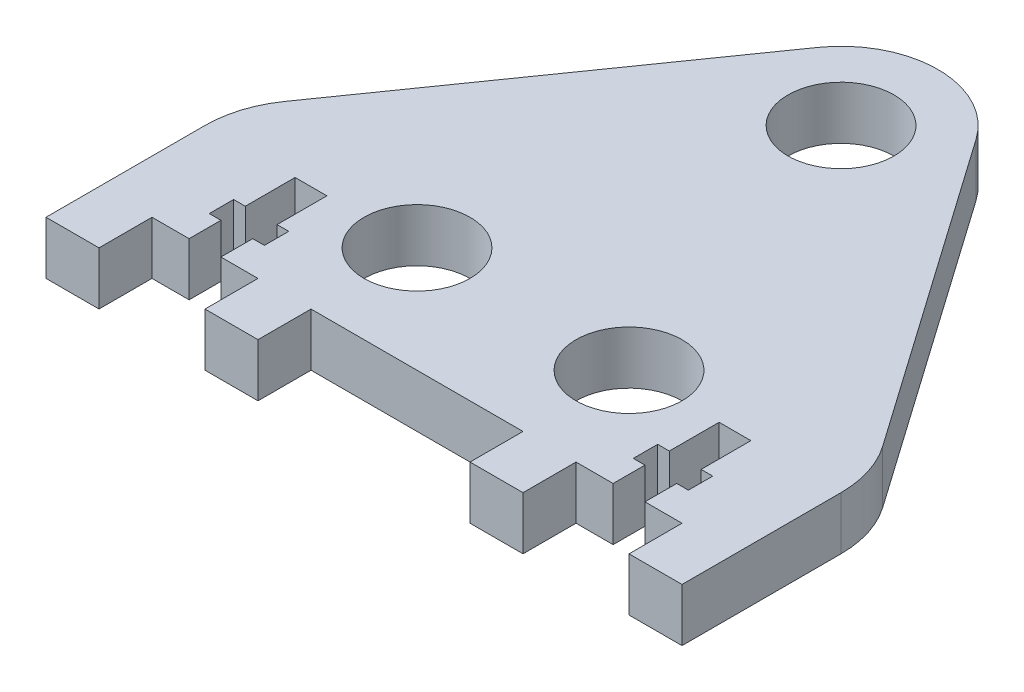
SolidWorks part; units mm, degrees
ref_plane "Front Plane" through (0, 0, 0) normal (0, 0, 1) x (1, 0, 0)
ref_plane "Top Plane" through (0, 0, 0) normal (0, 1, 0) x (1, 0, 0)
ref_plane "Right Plane" through (0, 0, 0) normal (1, 0, 0) x (0, 0, -1)
sketch "Sketch1" plane through (0, 0, 0) normal (0, 1, 0) x (1, 0, 0)
  line L1 (-30, 10) -> (-30, -5)
  line L2 (-30, -5) -> (-25, -5)
  line L3 (-10, -5) -> (-10, 0)
  line L4 (-10, 0) -> (10, 0)
  line L5 (10, -5) -> (10, 0)
  line L6 (30, -5) -> (25, -5)
  line L7 (30, 10) -> (30, -5)
  line L11 (0, 0) -> (0, 43.6328) construction
  line L13 (-28.1874, 15.7417) -> (-7.4911, 45.2534)
  line L14 (7.4911, 45.2534) -> (28.1874, 15.7417)
  line L36 (-25, -5) -> (-25, 0)
  line L37 (-25, 0) -> (-21.5, 0)
  line L38 (-21.5, 0) -> (-21.5, 3)
  line L39 (-21.5, 3) -> (-22.6, 3)
  line L40 (-22.6, 3) -> (-22.6, 5.3)
  line L41 (-22.6, 5.3) -> (-21.5, 5.3)
  line L42 (-21.5, 5.3) -> (-21.5, 10)
  line L43 (-21.5, 10) -> (-18.5, 10)
  line L44 (-18.5, 10) -> (-18.5, 5.3)
  line L45 (-18.5, 5.3) -> (-17.4, 5.3)
  line L46 (-17.4, 5.3) -> (-17.4, 3)
  line L47 (-17.4, 3) -> (-18.5, 3)
  line L48 (-18.5, 3) -> (-18.5, 0)
  line L49 (-18.5, 0) -> (-15, 0)
  line L50 (-15, 0) -> (-15, -5)
  line L51 (-15, -5) -> (-10, -5)
  line L52 (25, 0) -> (21.5, 0)
  line L53 (21.5, 0) -> (21.5, 3)
  line L54 (21.5, 3) -> (22.6, 3)
  line L55 (22.6, 5.3) -> (21.5, 5.3)
  line L56 (22.6, 3) -> (22.6, 5.3)
  line L57 (21.5, 5.3) -> (21.5, 10)
  line L58 (21.5, 10) -> (18.5, 10)
  line L59 (18.5, 10) -> (18.5, 5.3)
  line L60 (18.5, 5.3) -> (17.4, 5.3)
  line L61 (17.4, 5.3) -> (17.4, 3)
  line L62 (17.4, 3) -> (18.5, 3)
  line L63 (18.5, 3) -> (18.5, 0)
  line L64 (18.5, 0) -> (15, 0)
  line L65 (15, 0) -> (15, -5)
  line L66 (25, -5) -> (25, 0)
  line L67 (15, -5) -> (10, -5)
  arc A0 (-7.4911, 45.2534) -> (7.4911, 45.2534) centre (0, 40) cw
  circle A2 centre (0, 40) radius 5
  arc A3 (30, 10) -> (28.1874, 15.7417) centre (20, 10) ccw
  arc A4 (-30, 10) -> (-28.1874, 15.7417) centre (-20, 10) cw
  circle A5 centre (-10, 10) radius 5
  circle A6 centre (10, 10) radius 5
  point P0 (0, 0)
  point P68 (-16.75, 0)
  point P72 (-17.95, 3)
  point P73 (-22.05, 5.3)
  point P74 (-22.05, 3)
  point P78 (22.05, 3)
  point P80 (22.05, 5.3)
  point P88 (17.95, 3)
  point P91 (16.75, 0)
  dimension "D1" = 5
  dimension "D4" = 10
  dimension "D6" = 60
  dimension "D24" = 10
  dimension "D2" = 5
  dimension "D3" = 40
  dimension "D5" = 10
  dimension "D7" = 10
  dimension "D12" = 5
  dimension "D13" = 5
  dimension "D15" = 2.3
  dimension "D16" = 3
  dimension "D17" = 10
  dimension "D18" = 3
  dimension "D19" = 3.5
  dimension "D20" = 5.2
  dimension "D21" = 2.6
  dimension "D22" = 10
  dimension "D23" = 10
extrude "Boss-Extrude1" add sketch "Sketch1" along normal blind 5
